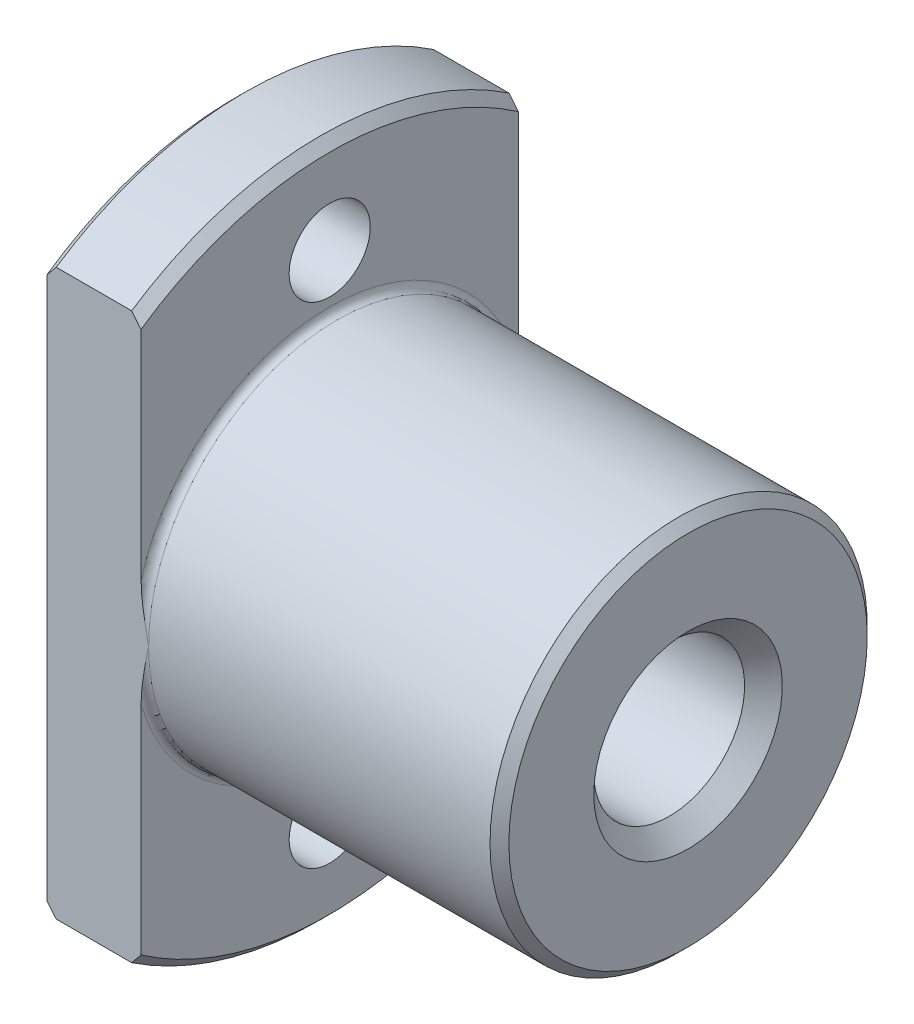
SolidWorks part; units mm, degrees
ref_plane "Front Plane" through (0, 0, 0) normal (0, 0, 1) x (1, 0, 0)
ref_plane "Top Plane" through (0, 0, 0) normal (0, 1, 0) x (1, 0, 0)
ref_plane "Right Plane" through (0, 0, 0) normal (1, 0, 0) x (0, 0, -1)
ref_plane "Plane1" through (0, 0, 0) normal (0, 0, 1) x (1, 0, 0)
sketch "Sketch1" plane through (0, 0, 0) normal (0, 0, 1) x (1, 0, 0)
  line L0 (0, 0) -> (0, 17.5)
  line L1 (0, 17.5) -> (0.5, 18)
  line L2 (0.5, 18) -> (4.5, 18)
  line L3 (4.5, 18) -> (5, 17.5)
  line L4 (5, 17.5) -> (5, 10.4)
  line L5 (5.4, 10) -> (23.5, 10)
  line L6 (23.5, 10) -> (24, 9.5)
  line L7 (24, 9.5) -> (24, 0)
  line L8 (24, 0) -> (0, 0)
  line L9 (24, 0) -> (0, 0) construction
  arc A0 (5, 10.4) -> (5.4, 10) centre (5.4, 10.4) ccw
revolve "Revolve1" add sketch "Sketch1" angle 360 about L9
ref_plane "Plane2" through (0, 0, 0) normal (0, 0, 1) x (1, 0, 0)
sketch "Sketch2" plane through (0, 0, 0) normal (0, 0, 1) x (1, 0, 0)
  line L0 (0, 0) -> (0, 5)
  line L1 (0, 5) -> (1, 4)
  line L2 (1, 4) -> (23, 4)
  line L3 (23, 4) -> (24, 5)
  line L4 (24, 5) -> (24, 0)
  line L5 (24, 0) -> (0, 0)
  line L6 (24, 0) -> (0, 0) construction
revolve "Cut-Revolve1" cut sketch "Sketch2" angle 360 about L6
cosmetic thread "Cosmetic Thread1" parameters "D1"=24, "D2"=10
ref_plane "Plane3" through (0, 0, 0) normal (0, 0, 1) x (1, 0, 0)
sketch "Sketch3" plane through (0, 0, 0) normal (0, 0, 1) x (1, 0, 0)
  line L0 (0, 13) -> (0, 15.15)
  line L1 (0, 15.15) -> (5, 15.15)
  line L2 (5, 15.15) -> (5, 13)
  line L3 (5, 13) -> (0, 13)
  line L4 (5, 13) -> (0, 13) construction
revolve "Cut-Revolve2" cut sketch "Sketch3" angle 360 about L4
ref_plane "Plane4" through (0, 0, 0) normal (0, 0, 1) x (1, 0, 0)
sketch "Sketch4" plane through (0, 0, 0) normal (0, 0, 1) x (1, 0, 0)
  line L0 (0, -13) -> (0, -10.85)
  line L1 (0, -10.85) -> (5, -10.85)
  line L2 (5, -10.85) -> (5, -13)
  line L3 (5, -13) -> (0, -13)
  line L4 (5, -13) -> (0, -13) construction
revolve "Cut-Revolve3" cut sketch "Sketch4" angle 360 about L4
ref_plane "Plane5" through (0, 0, 0) normal (1, 0, 0) x (0, 0, -1)
sketch "Sketch5" plane through (0, 0, 0) normal (1, 0, 0) x (0, 0, -1)
  line L0 (-20, -54) -> (20, -54)
  line L1 (20, -54) -> (20, 54)
  line L2 (20, 54) -> (-20, 54)
  line L3 (-20, 54) -> (-20, -54)
  line L4 (-10, -36) -> (10, -36)
  line L5 (10, -36) -> (10, 36)
  line L6 (10, 36) -> (-10, 36)
  line L7 (-10, 36) -> (-10, -36)
extrude "Cut-Extrude1" cut sketch "Sketch5" against normal blind 7.5 and the other way blind 7.5
